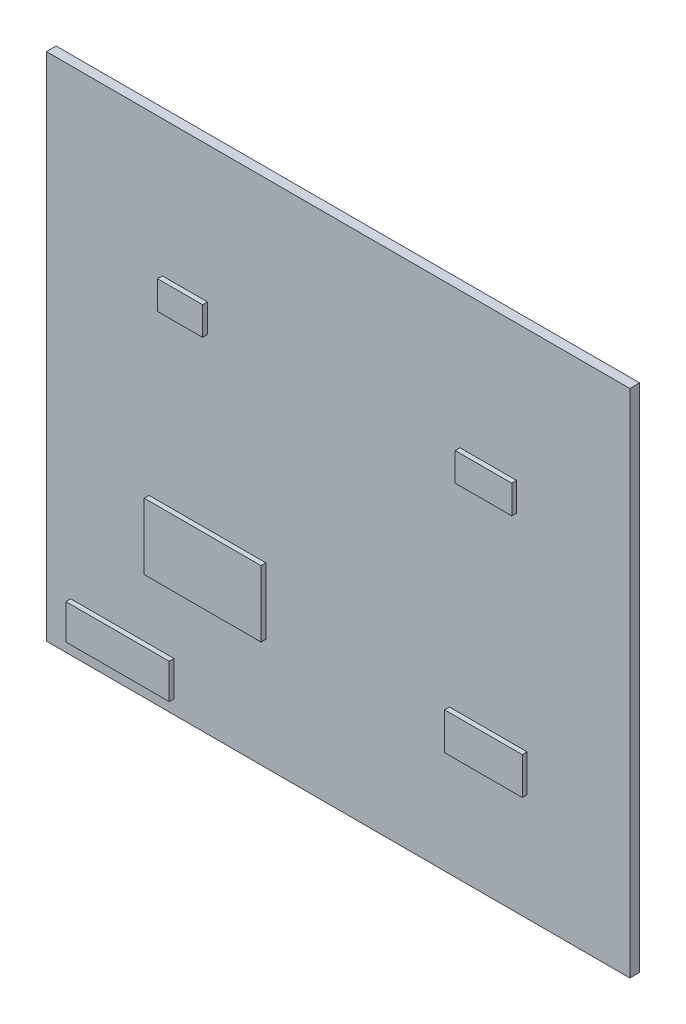
SolidWorks part; units mm, degrees
material "Custom Plastic"
ref_plane "Plan de face" through (0, 0, 0) normal (0, 0, 1) x (1, 0, 0)
ref_plane "Plan de dessus" through (0, 0, 0) normal (0, 1, 0) x (1, 0, 0)
ref_plane "Plan de droite" through (0, 0, 0) normal (1, 0, 0) x (0, 0, -1)
sketch "Sketch1" plane through (0, 0, 0) normal (0, 0, 1) x (1, 0, 0)
  line L1 (-60, -52.5) -> (60, -52.5)
  line L2 (-60, -52.5) -> (-60, 52.5)
  line L3 (-60, 52.5) -> (60, 52.5)
  line L4 (60, -52.5) -> (60, 52.5)
  line L5 (-60, -52.5) -> (60, 52.5) construction
  line L6 (-60, 52.5) -> (60, -52.5) construction
  point P0 (0, 0)
  dimension "D1" = 120
  dimension "D2" = 105
extrude "Boss-Extrude1" add sketch "Sketch1" along normal blind 2
sketch "Sketch2" plane through (0, 0, 2) normal (0, 0, 1) x (1, 0, 0)
  line L1 (-38.8763, -29.5865) -> (-14.8556, -29.5865)
  line L2 (-38.8763, -29.5865) -> (-38.8763, -15.9818)
  line L3 (-38.8763, -15.9818) -> (-14.8556, -15.9818)
  line L4 (-14.8556, -29.5865) -> (-14.8556, -15.9818)
  line L5 (-38.8763, -29.5865) -> (-14.8556, -15.9818) construction
  line L6 (-38.8763, -15.9818) -> (-14.8556, -29.5865) construction
  line L7 (22.8955, -30.418) -> (38.8724, -30.418)
  line L8 (22.8955, -30.418) -> (22.8955, -22.7841)
  line L9 (22.8955, -22.7841) -> (38.8724, -22.7841)
  line L10 (38.8724, -30.418) -> (38.8724, -22.7841)
  line L11 (22.8955, -30.418) -> (38.8724, -22.7841) construction
  line L12 (22.8955, -22.7841) -> (38.8724, -30.418) construction
  line L13 (-36.1531, 18.6658) -> (-26.866, 18.6658)
  line L14 (-36.1531, 18.6658) -> (-36.1531, 24.4802)
  line L15 (-36.1531, 24.4802) -> (-26.866, 24.4802)
  line L16 (-26.866, 18.6658) -> (-26.866, 24.4802)
  line L17 (-36.1531, 18.6658) -> (-26.866, 24.4802) construction
  line L18 (-36.1531, 24.4802) -> (-26.866, 18.6658) construction
  line L19 (25.0598, 18.6658) -> (36.7081, 18.6658)
  line L20 (25.0598, 18.6658) -> (25.0598, 24.4802)
  line L21 (25.0598, 24.4802) -> (36.7081, 24.4802)
  line L22 (36.7081, 18.6658) -> (36.7081, 24.4802)
  line L23 (25.0598, 18.6658) -> (36.7081, 24.4802) construction
  line L24 (25.0598, 24.4802) -> (36.7081, 18.6658) construction
  line L25 (-55.0149, -49.6479) -> (-33.7473, -49.6479)
  line L26 (-55.0149, -49.6479) -> (-55.0149, -42.458)
  line L27 (-55.0149, -42.458) -> (-33.7473, -42.458)
  line L28 (-33.7473, -49.6479) -> (-33.7473, -42.458)
  line L29 (-55.0149, -49.6479) -> (-33.7473, -42.458) construction
  line L30 (-55.0149, -42.458) -> (-33.7473, -49.6479) construction
  point P0 (-26.866, -22.7841)
  point P5 (30.8839, -26.6011)
  point P10 (-31.5095, 21.573)
  point P15 (30.8839, 21.573)
  point P20 (-44.3811, -46.0529)
extrude "Boss-Extrude2" add sketch "Sketch2" along normal blind 1
